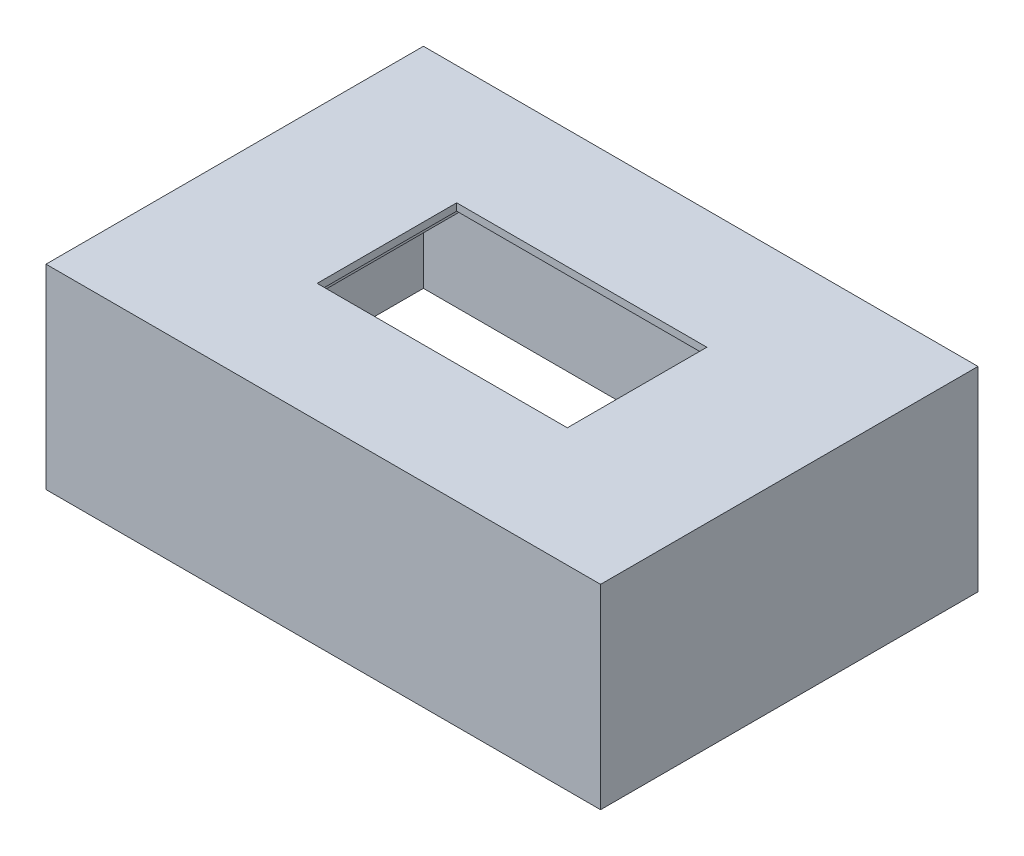
SolidWorks part; units mm, degrees
ref_plane "Спереди" through (0, 0, 0) normal (0, 0, 1) x (1, 0, 0)
ref_plane "Сверху" through (0, 0, 0) normal (0, 1, 0) x (1, 0, 0)
ref_plane "Справа" through (0, 0, 0) normal (1, 0, 0) x (0, 0, -1)
sketch "Эскиз1" plane through (0, 0, 0) normal (0, 1, 0) x (1, 0, 0)
  line L1 (-56.9401, -5.625) -> (19.7599, -5.625)
  line L2 (-56.9401, -5.625) -> (-56.9401, -57.825)
  line L3 (-56.9401, -57.825) -> (19.7599, -57.825)
  line L4 (19.7599, -5.625) -> (19.7599, -57.825)
  line L5 (-54.9401, -7.625) -> (17.7599, -7.625)
  line L6 (-54.9401, -7.625) -> (-54.9401, -55.825)
  line L7 (-54.9401, -55.825) -> (17.7599, -55.825)
  line L8 (17.7599, -7.625) -> (17.7599, -55.825)
  dimension "D1" = 2
  dimension "D2" = 2
  dimension "D3" = 2
  dimension "D4" = 2
  dimension "D5" = 72.7
  dimension "D6" = 48.2
extrude "Бобышка-Вытянуть1" add sketch "Эскиз1" along normal blind 25
sketch "Эскиз2" plane through (0, 25, 0) normal (0, 1, 0) x (1, 0, 0)
  line L1 (-56.9401, -5.625) -> (19.7599, -5.625)
  line L2 (-56.9401, -5.625) -> (-56.9401, -57.825)
  line L3 (-56.9401, -57.825) -> (19.7599, -57.825)
  line L4 (19.7599, -5.625) -> (19.7599, -57.825)
extrude "Бобышка-Вытянуть2" add sketch "Эскиз2" along normal blind 2
sketch "Эскиз3" plane through (0, 27, 0) normal (0, 1, 0) x (1, 0, 0)
  line L0 (-18.5901, -5.625) -> (-18.5901, -57.825) construction
  line L1 (19.7599, -5.625) -> (-56.9401, -5.625) construction
  line L2 (-56.9401, -57.825) -> (19.7599, -57.825) construction
  line L3 (-56.9401, -31.725) -> (19.7599, -31.725) construction
  line L4 (-56.9401, -5.625) -> (-56.9401, -57.825) construction
  line L5 (19.7599, -57.825) -> (19.7599, -5.625) construction
  line L7 (-35.8901, -22.075) -> (-1.2901, -22.075)
  line L8 (-35.8901, -22.075) -> (-35.8901, -41.375)
  line L9 (-35.8901, -41.375) -> (-1.2901, -41.375)
  line L10 (-1.2901, -22.075) -> (-1.2901, -41.375)
  point P16 (-18.5901, -22.075)
  point P17 (-35.8901, -31.725)
  dimension "D1" = 34.6
  dimension "D2" = 19.3
extrude "Вырез-Вытянуть1" cut sketch "Эскиз3" against normal up to surface (2 mm away) up to face at (-18.5901, 25, 31.725)
sketch "Эскиз4" plane through (0, 25, 0) normal (0, -1, 0) x (1, 0, 0)
  line L0 (-18.5901, 52.7516) -> (-18.5901, 13.4773) construction
  line L1 (-42.8124, 31.725) -> (12.4867, 31.725) construction
  line L2 (-1.2901, 41.375) -> (-35.8901, 41.375) construction
  line L3 (-36.5901, 48.875) -> (-0.5901, 48.875)
  line L4 (-36.5901, 48.875) -> (-36.5901, 14.575)
  line L5 (-36.5901, 14.575) -> (-0.5901, 14.575)
  line L6 (-0.5901, 48.875) -> (-0.5901, 14.575)
  line L7 (-1.2901, 22.075) -> (-1.2901, 41.375) construction
  point P8 (-18.5901, 48.875)
  point P11 (-18.5901, 41.375)
  point P12 (-36.5901, 31.725)
  point P15 (-1.2901, 31.725)
  dimension "D1" = 36
  dimension "D2" = 34.3
extrude "Вырез-Вытянуть2" cut sketch "Эскиз4" against normal blind 1
chamfer "Фаска1" distance 2 angle 45 4 edges at (-18.5901, 25, 7.625) (17.7599, 25, 31.725) (-54.9401, 25, 31.725) (-18.5901, 25, 55.825)
sketch "Эскиз5" plane through (-56.9401, 0, 0) normal (-1, 0, 0) x (0, 0, 1)
  line L0 (35.6283, 11.5458) -> (35.6283, 0)
  line L1 (5.625, 0) -> (57.825, 0) construction
  line L2 (27.1283, 11.5458) -> (27.1283, 0)
  line L3 (27.1283, 0) -> (35.6283, 0)
  arc A0 (35.6283, 11.5458) -> (27.1283, 11.5458) centre (31.3783, 11.5458) ccw
  dimension "D1" = 8.5
extrude "Вырез-Вытянуть3" cut sketch "Эскиз5" against normal up to surface (2 mm away) up to face at (-54.9401, 11.5, 31.725)
